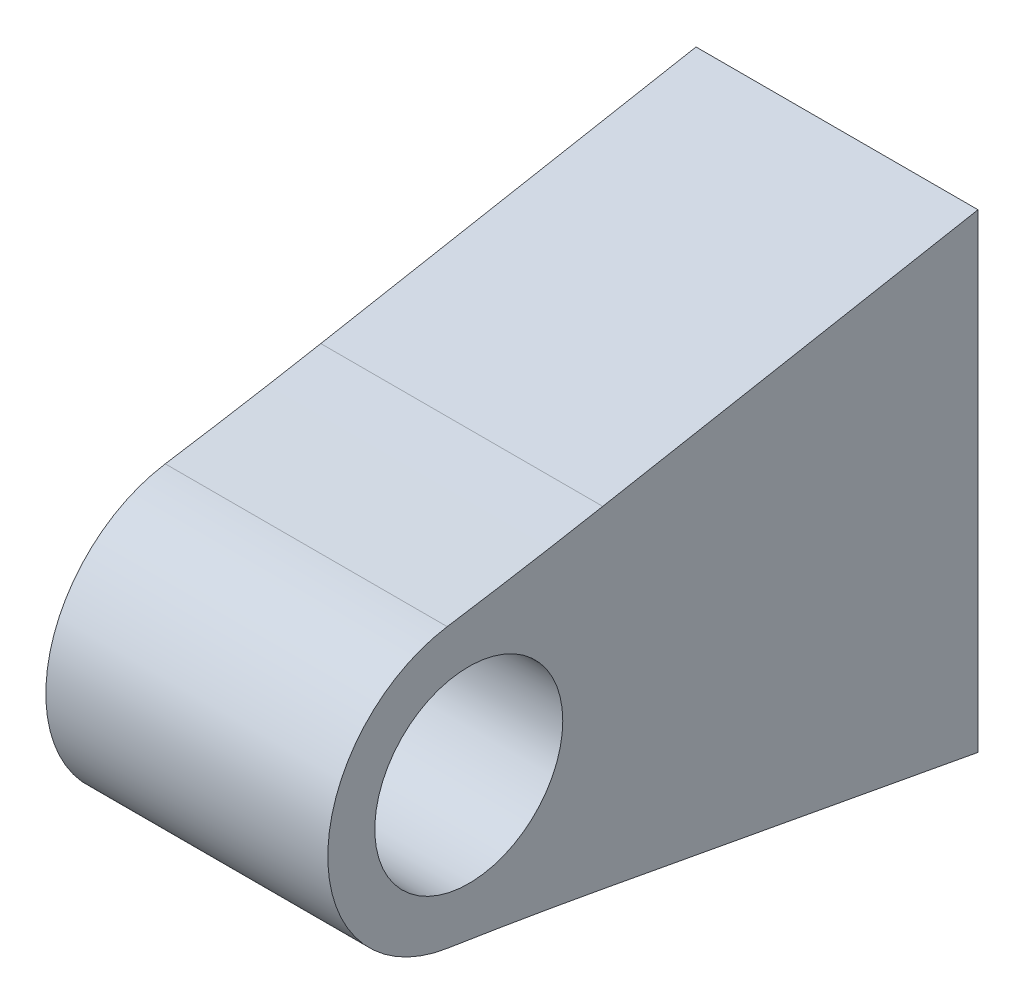
SolidWorks part; units mm, degrees
ref_plane "Front Plane" through (0, 0, 0) normal (0, 0, 1) x (1, 0, 0)
ref_plane "Top Plane" through (0, 0, 0) normal (0, 1, 0) x (1, 0, 0)
ref_plane "Right Plane" through (0, 0, 0) normal (1, 0, 0) x (0, 0, -1)
sketch "Sketch1" plane through (0, 0, 0) normal (1, 0, 0) x (0, 0, -1)
  line L5 (0.7402, 0.6169) -> (0, 0) construction
  line L6 (0.7402, -0.6169) -> (0, 0) construction
  line L8 (-4.2216, 7.5) -> (22.867, 12.5)
  line L9 (22.867, 12.5) -> (22.867, -12.5)
  line L10 (22.867, -12.5) -> (-4.2216, -7.5)
  circle A0 centre (-4.2216, 0) radius 5
  arc A1 (-4.2216, 7.5) -> (-4.2216, -7.5) centre (-4.2216, 0) ccw
  point P0 (0, 0)
  dimension "D3" = 10
  dimension "D4" = 15
  dimension "D1" = 25
extrude "Boss-Extrude1" add sketch "Sketch1" along normal blind 15
fillet "Fillet1" radius 290 2 edges at (7.5, -7.5, 4.2216) (7.5, 7.5, 4.2216)
sketch "Sketch3" plane through (0, 0, -22.867) normal (0, 0, -1) x (-1, 0, 0)
  circle A0 centre (-7.5, 0) radius 2.5
  dimension "D1" = 5
  dimension "D2" = 7.5
extrude "Cut-Extrude2" cut sketch "Sketch3" against normal blind 5
